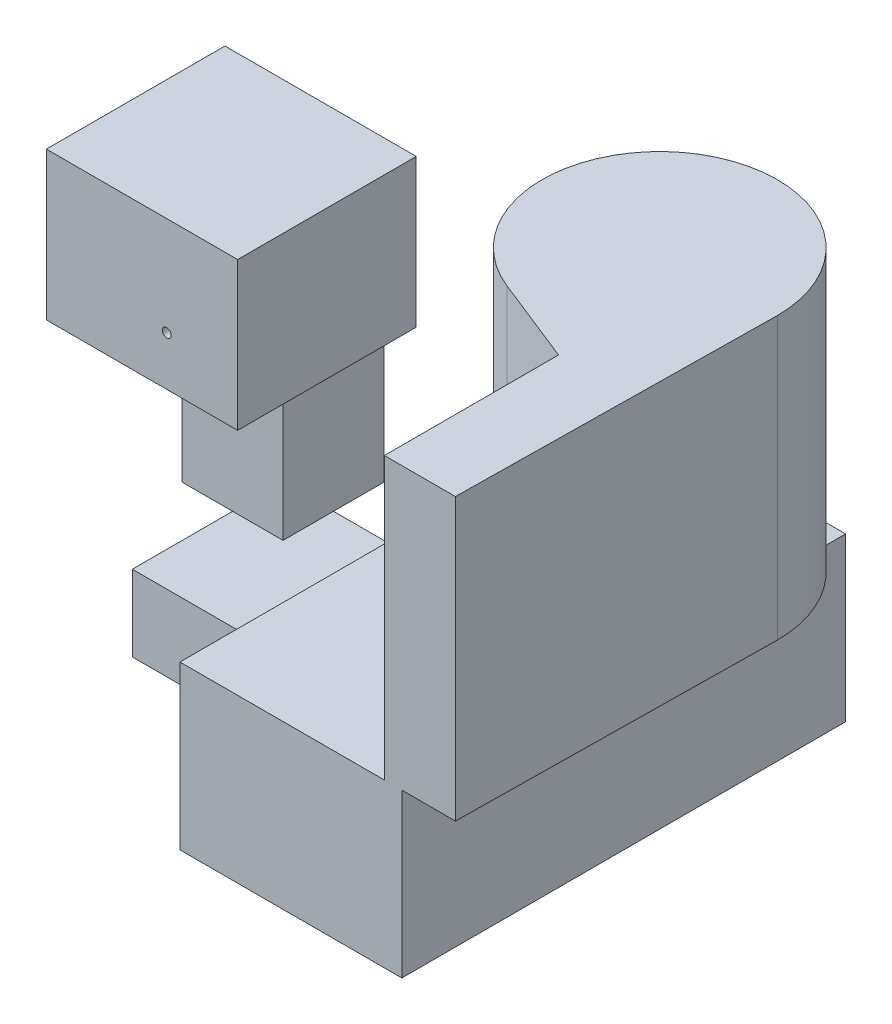
SolidWorks part; units mm, degrees
ref_plane "Front Plane" through (0, 0, 0) normal (0, 0, 1) x (1, 0, 0)
ref_plane "Top Plane" through (0, 0, 0) normal (0, 1, 0) x (1, 0, 0)
ref_plane "Right Plane" through (0, 0, 0) normal (1, 0, 0) x (0, 0, -1)
sketch "Sketch1" plane through (0, 0, 0) normal (0, 1, 0) x (1, 0, 0)
  line L0 (0, 300) -> (0, 0)
  line L1 (0, -55) -> (0, 55) construction
  line L2 (0, 0) -> (150, 0)
  line L3 (150, 0) -> (150, 300)
  line L4 (150, 300) -> (0, 300)
  dimension "D1" = 300
  dimension "D2" = 150
extrude "Boss-Extrude1" add sketch "Sketch1" against normal blind 110
sketch "Sketch2" plane through (0, 0, 0) normal (0, 1, 0) x (1, 0, 0)
  line L0 (30, 214.7921) -> (30, 131.6005) construction
  line L2 (-60.5, 0) -> (60.5, 0) construction
  line L3 (80.0638, 140.9108) -> (138.2006, 117.7109)
  line L4 (138.2006, 117.7109) -> (138.2006, 0)
  line L5 (138.2006, 0) -> (186.2291, 0)
  line L6 (186.2291, 0) -> (189.0934, 214.7921)
  line L7 (0, -60.5) -> (0, 60.5) construction
  arc A0 (189.0934, 214.7921) -> (80.0638, 140.9108) centre (109.5467, 214.7921) ccw
  dimension "D1" = 30
extrude "Boss-Extrude2" add sketch "Sketch2" along normal blind 190
sketch "Sketch3" plane through (0, 0, 0) normal (-1, 0, 0) x (0, 0, 1)
  line L1 (-67.7972, -80.9493) -> (-169.6944, -80.9493)
  line L2 (-67.7972, -80.9493) -> (-67.7972, -29.5726)
  line L3 (-67.7972, -29.5726) -> (-169.6944, -29.5726)
  line L4 (-169.6944, -80.9493) -> (-169.6944, -29.5726)
  line L5 (-67.7972, -80.9493) -> (-169.6944, -29.5726) construction
  line L6 (-67.7972, -29.5726) -> (-169.6944, -80.9493) construction
  point P0 (-118.7458, -55.261)
extrude "Boss-Extrude3" add sketch "Sketch3" along normal blind 100
sketch "Sketch4" plane through (0, -29.5726, 0) normal (0, 1, 0) x (1, 0, 0)
  line L1 (-134.0868, 203.7812) -> (-65.9132, 203.7812)
  line L2 (-134.0868, 203.7812) -> (-134.0868, 135.6076)
  line L3 (-134.0868, 135.6076) -> (-65.9132, 135.6076)
  line L4 (-65.9132, 203.7812) -> (-65.9132, 135.6076)
  line L5 (-134.0868, 203.7812) -> (-65.9132, 135.6076) construction
  line L6 (-134.0868, 135.6076) -> (-65.9132, 203.7812) construction
  point P0 (-100, 169.6944)
extrude "Boss-Extrude4" add sketch "Sketch4" along normal blind 100
sketch "Sketch5" plane through (0, 70.4274, 0) normal (0, 1, 0) x (1, 0, 0)
  line L1 (-175.0066, 205.444) -> (-45.7085, 205.444)
  line L2 (-175.0066, 205.444) -> (-175.0066, 84.7087)
  line L3 (-175.0066, 84.7087) -> (-45.7085, 84.7087)
  line L4 (-45.7085, 205.444) -> (-45.7085, 84.7087)
  line L5 (-175.0066, 205.444) -> (-45.7085, 84.7087) construction
  line L6 (-175.0066, 84.7087) -> (-45.7085, 205.444) construction
  point P0 (-110.3575, 145.0764)
extrude "Boss-Extrude5" add sketch "Sketch5" along normal blind 100
sketch "Sketch6" plane through (0, 0, -84.7087) normal (0, 0, 1) x (1, 0, 0)
  circle A0 centre (-93.6259, 103.6126) radius 3
  dimension "D1" = 6
extrude "Cut-Extrude1" cut sketch "Sketch6" against normal blind 160
